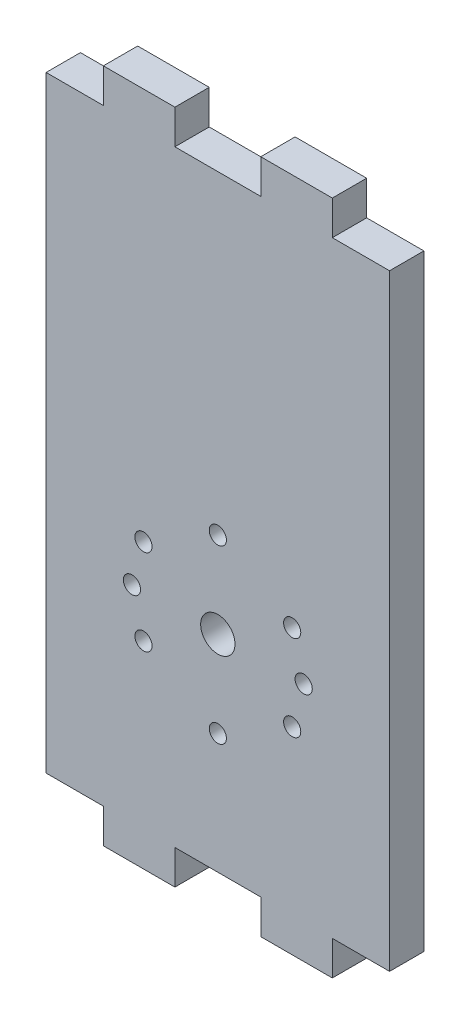
SolidWorks part; units mm, degrees
ref_plane "Alzado" through (0, 0, 0) normal (0, 0, 1) x (1, 0, 0)
ref_plane "Planta" through (0, 0, 0) normal (0, 1, 0) x (1, 0, 0)
ref_plane "Vista lateral" through (0, 0, 0) normal (1, 0, 0) x (0, 0, -1)
sketch "Sketch1" plane through (0, 0, 0) normal (0, 0, 1) x (1, 0, 0)
  line L0 (-15, 26.5) -> (-10, 26.5)
  line L1 (-10, 29.5) -> (-3.75, 29.5)
  line L2 (-15, 26.5) -> (-15, -26.5)
  line L3 (-10, -29.5) -> (-3.75, -29.5)
  line L4 (15, 26.5) -> (15, -26.5)
  line L5 (-15, 29.5) -> (15, -29.5) construction
  line L6 (-15, -29.5) -> (15, 29.5) construction
  line L7 (-10, 26.5) -> (-10, 29.5)
  line L8 (-3.75, 29.5) -> (-3.75, 26.5)
  line L9 (-3.75, 26.5) -> (3.75, 26.5)
  line L10 (3.75, 26.5) -> (3.75, 29.5)
  line L11 (10, 29.5) -> (10, 26.5)
  line L12 (10, 26.5) -> (15, 26.5)
  line L13 (-15, 0) -> (15, 0) construction
  line L14 (0, 26.5) -> (0, 0) construction
  line L15 (10, -26.5) -> (15, -26.5)
  line L16 (10, -29.5) -> (10, -26.5)
  line L17 (-3.75, -29.5) -> (-3.75, -26.5)
  line L18 (3.75, -26.5) -> (3.75, -29.5)
  line L19 (-3.75, -26.5) -> (3.75, -26.5)
  line L20 (-10, -26.5) -> (-10, -29.5)
  line L21 (-15, -26.5) -> (-10, -26.5)
  line L22 (3.75, 29.5) -> (10, 29.5)
  line L23 (3.75, -29.5) -> (10, -29.5)
  line L24 (-15, 26.5) -> (-15, 29.5) construction
  line L25 (-15, 29.5) -> (-10, 29.5) construction
  line L26 (15, 26.5) -> (15, 29.5) construction
  line L27 (15, 29.5) -> (10, 29.5) construction
  line L28 (-15, -26.5) -> (-15, -29.5) construction
  line L29 (-15, -29.5) -> (-10, -29.5) construction
  line L30 (15, -26.5) -> (15, -29.5) construction
  line L31 (15, -29.5) -> (10, -29.5) construction
  line L32 (0, 0) -> (0, -8.5) construction
  line L33 (-6.4952, -4.75) -> (6.4952, -12.25) construction
  line L34 (6.4952, -4.75) -> (-6.4952, -12.25) construction
  line L35 (0, -8.5) -> (0, -16) construction
  circle A0 centre (0, -8.5) radius 7.5 construction
  circle A1 centre (0, -1) radius 0.75
  circle A2 centre (6.4952, -4.75) radius 0.75
  circle A3 centre (6.4952, -12.25) radius 0.75
  circle A4 centre (0, -16) radius 0.75
  circle A5 centre (-6.4952, -12.25) radius 0.75
  circle A6 centre (-6.4952, -4.75) radius 0.75
  circle A7 centre (0, -8.5) radius 1.5
  circle A8 centre (-7.5, -8.5) radius 0.75
  circle A9 centre (7.5, -8.5) radius 0.75
  point P5 (0, 0)
  point P45 (0.3377, -8.3921)
  dimension "D7" = 8.5
  dimension "D8" = 60
  dimension "D9" = 3
  dimension "D10" = 1.5
  dimension "D11" = 15
  dimension "D1" = 59
  dimension "D2" = 30
  dimension "D3" = 3
  dimension "D4" = 5
  dimension "D5" = 5
  dimension "D6" = 7.5
  dimension "D12" = 60
extrude "Boss-Extrude1" add sketch "Sketch1" along normal blind 3
